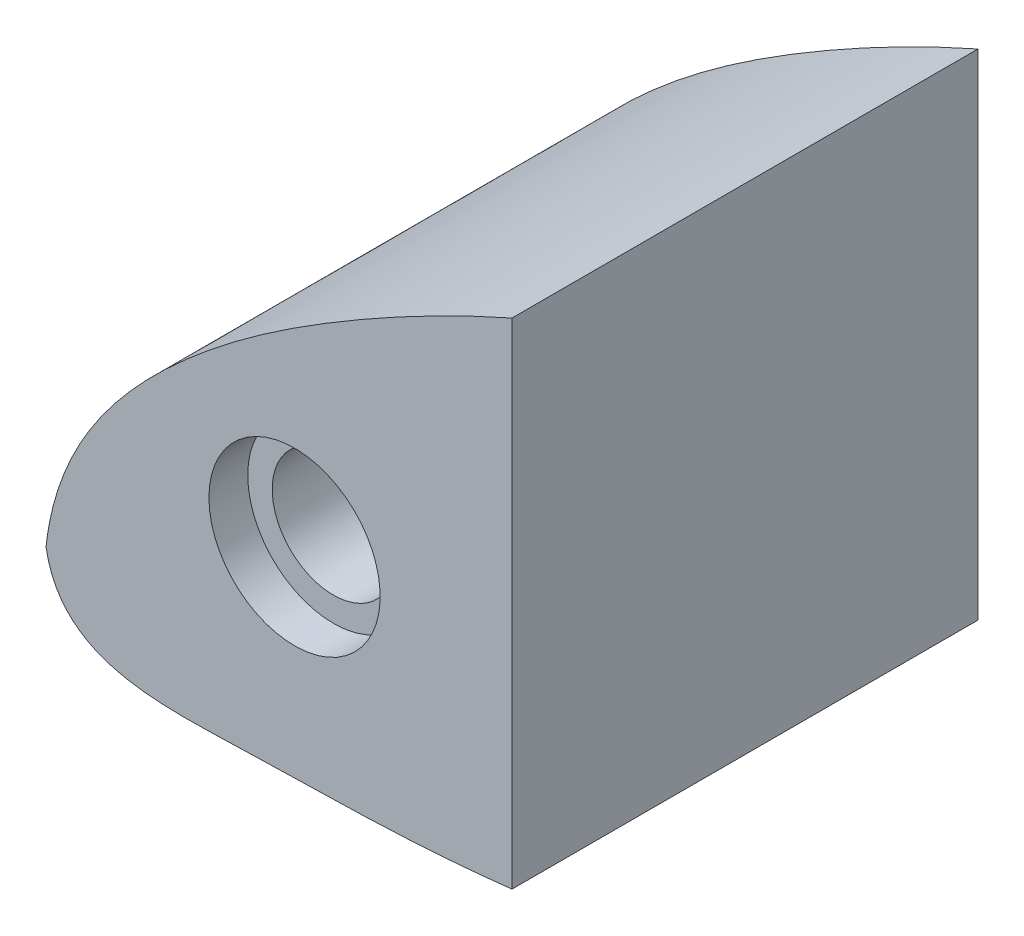
SolidWorks part; units mm, degrees
ref_plane "Front Plane" through (0, 0, 0) normal (0, 0, 1) x (1, 0, 0)
ref_plane "Top Plane" through (0, 0, 0) normal (0, 1, 0) x (1, 0, 0)
ref_plane "Right Plane" through (0, 0, 0) normal (1, 0, 0) x (0, 0, -1)
sketch "Sketch1" plane through (0, 0, 0) normal (0, 0, 1) x (1, 0, 0)
  spline S0 degree 3 poles (0.0006, 0.0001) (0.8106, 7.3592) (8.6491, 17.8566) (26.2867, 29.9752) (52.1111, 42.0692) (89.5976, 49.2908) (131.4008, 47.8848) (173.2567, 40.0411) (217.9611, 29.613) (256.9521, 19.5289) (290.3598, 8.711) (301.2732, 4.3828) (314.8169, -0.5162) (309.8463, 0.0001) knots 0 0 0 0 0.060864 0.113688 0.188609 0.312909 0.448482 0.557612 0.691544 0.852438 0.929756 0.976058 1 1 1 1
  spline S1 degree 3 poles (309.8463, 0.0001) (303.9568, 1.471) (293.9895, 2.094) (276.264, 4.5144) (260.8463, 5.4274) (235.8588, 7.8703) (205.1014, 8.8381) (157.7186, 9.0307) (110.4973, 6.1815) (66.5062, -0.5867) (36.4547, -6.0985) (15.3166, -6.1891) (1.2307, -6.9241) (0.0006, 0.0001) knots 0 0 0 0 0.057787 0.095275 0.171021 0.205339 0.335319 0.464904 0.658702 0.785512 0.893517 0.943092 1 1 1 1
extrude "Boss-Extrude1" add sketch "Sketch1" along normal blind 38.1
sketch "Sketch2" plane through (0, 0, 38.1) normal (0, 0, 1) x (1, 0, 0)
  circle A0 centre (20.32, 10.16) radius 5
  circle A1 centre (227.2963, 19.0501) radius 3.175
  dimension "D2" = 10
  dimension "D3" = 6.35
  dimension "D6" = 20.32
  dimension "D1" = 82.55
  dimension "D4" = 19.05
  dimension "D5" = 10.16
extrude "Cut-Extrude1" cut sketch "Sketch2" against normal through all
sketch "Sketch3" plane through (0, 0, 38.1) normal (0, 0, 1) x (1, 0, 0)
  line L1 (38.1, 71.718) -> (331.2889, 71.718)
  line L2 (38.1, 71.718) -> (38.1, -66.2532)
  line L3 (38.1, -66.2532) -> (331.2889, -66.2532)
  line L4 (331.2889, 71.718) -> (331.2889, -66.2532)
  dimension "D1" = 38.1
extrude "Cut-Extrude2" cut sketch "Sketch3" against normal through all
sketch "Sketch4" plane through (0, 0, 0) normal (0, 0, -1) x (-1, 0, 0)
  circle A0 centre (-20.32, 10.16) radius 7
  dimension "D1" = 14
extrude "Cut-Extrude3" cut sketch "Sketch4" against normal blind 3.175
mirror "Mirror1" about plane through (153.3878, 8.3334, 0) normal (0, 0, -1) of "Boss-Extrude1", "Cut-Extrude1", "Cut-Extrude2", "Cut-Extrude3"
sketch "Sketch5" plane through (38.1, 0, 0) normal (1, 0, 0) x (0, 0, -1)
  line L0 (-38.1, 35.2581) -> (38.1, 35.2581) construction
  line L1 (0, 35.2581) -> (-61.2162, 35.2581)
  line L2 (0, 35.2581) -> (0, -16.4371)
  line L3 (0, -16.4371) -> (-61.2162, -16.4371)
  line L4 (-61.2162, 35.2581) -> (-61.2162, -16.4371)
extrude "Cut-Extrude4" cut sketch "Sketch5" against normal through all
